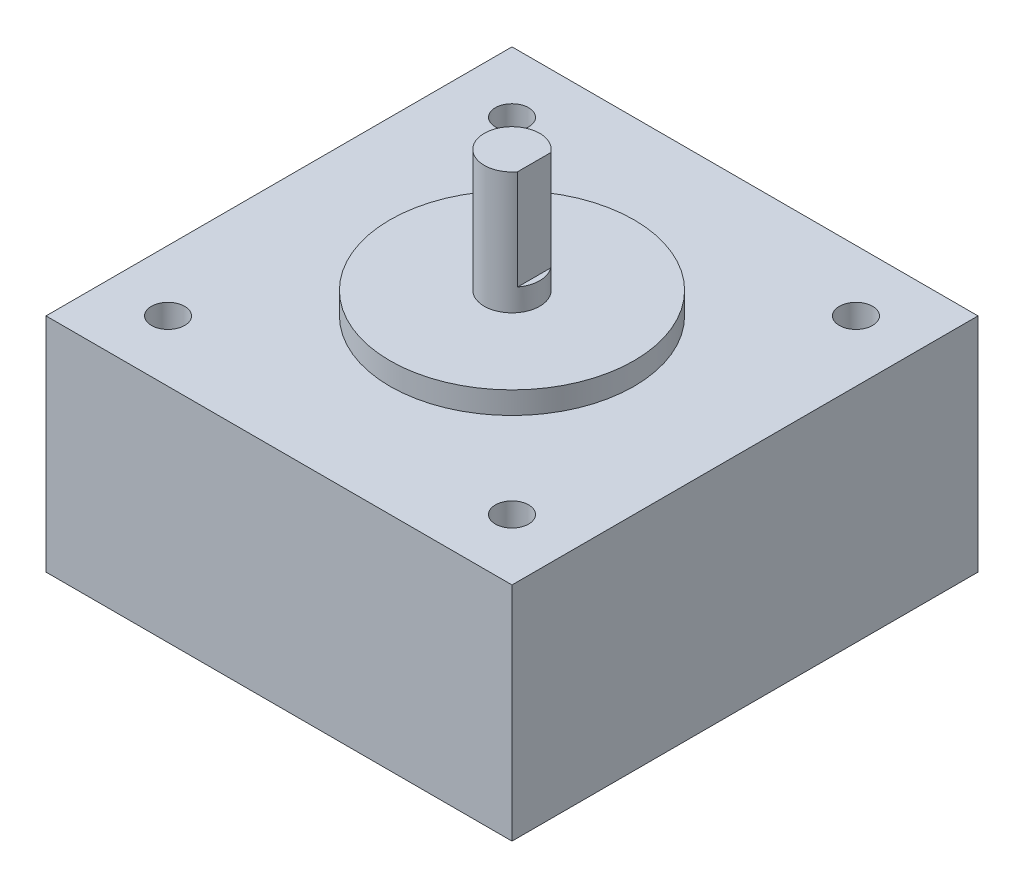
SolidWorks part; units mm, degrees
ref_plane "前视基准面" through (0, 0, 0) normal (0, 0, 1) x (1, 0, 0)
ref_plane "上视基准面" through (0, 0, 0) normal (0, 1, 0) x (1, 0, 0)
ref_plane "右视基准面" through (0, 0, 0) normal (1, 0, 0) x (0, 0, -1)
sketch "草图1" plane through (0, 0, 0) normal (0, 1, 0) x (1, 0, 0)
  line L1 (0, 0) -> (42, 0)
  line L2 (0, 0) -> (0, 42)
  line L3 (0, 42) -> (42, 42)
  line L4 (42, 0) -> (42, 42)
  circle A0 centre (5.5, 5.5) radius 1.5
  circle A1 centre (36.5, 5.5) radius 1.5
  circle A2 centre (36.5, 36.5) radius 1.5
  circle A3 centre (5.5, 36.5) radius 1.5
extrude "凸台-拉伸1" add sketch "草图1" along normal blind 20
sketch "草图2" plane through (0, 20, 0) normal (0, 1, 0) x (1, 0, 0)
  circle A0 centre (21, 21) radius 11
extrude "凸台-拉伸2" add sketch "草图2" along normal blind 2 contours A0
sketch "草图3" plane through (0, 22, 0) normal (0, 1, 0) x (1, 0, 0)
  circle A0 centre (21, 21) radius 2.5
extrude "凸台-拉伸3" add sketch "草图3" along normal blind 11 contours A0
sketch "草图4" plane through (0, 33, 0) normal (0, 1, 0) x (1, 0, 0)
  line L0 (18.5, 21) -> (23, 21)
  line L1 (23, 19.5) -> (23, 22.5)
  circle A0 centre (21, 21) radius 2.5 construction
  circle A1 centre (21, 21) radius 2.5 construction
  circle A2 centre (21, 21) radius 2.5
  circle M3 centre (21, 21) radius 2.5
extrude "切除-拉伸1" cut sketch "草图4" against normal blind 9 contours L1 M3
